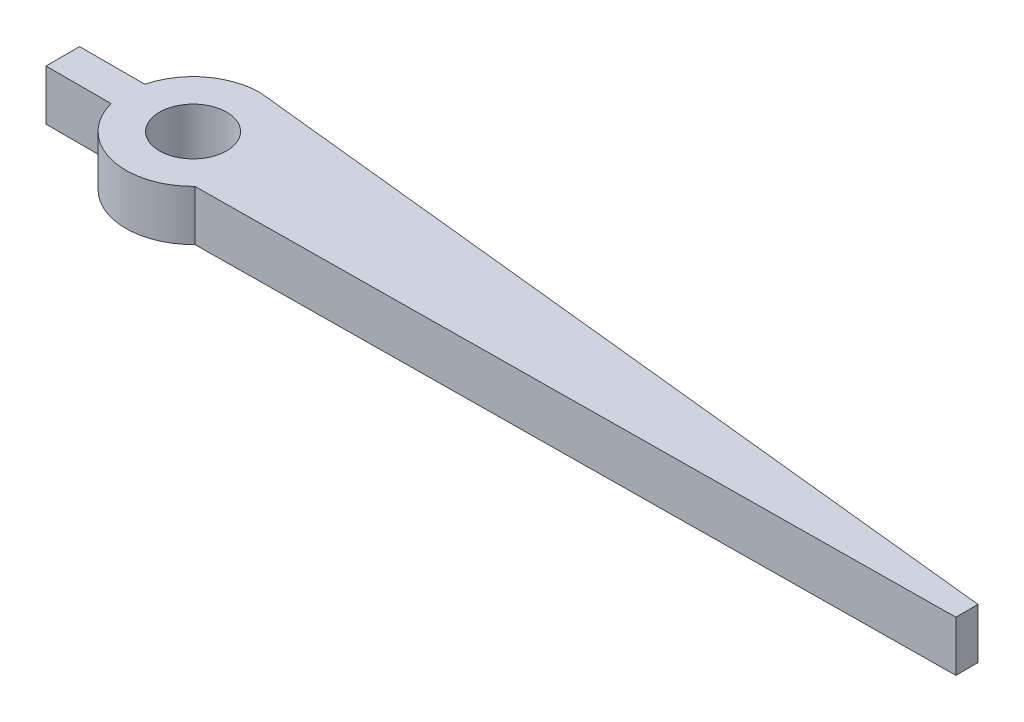
SolidWorks part; units mm, degrees
ref_plane "Front Plane" through (0, 0, 0) normal (0, 0, 1) x (1, 0, 0)
ref_plane "Top Plane" through (0, 0, 0) normal (0, 1, 0) x (1, 0, 0)
ref_plane "Right Plane" through (0, 0, 0) normal (1, 0, 0) x (0, 0, -1)
sketch "Sketch1" plane through (0, 0, 0) normal (0, 1, 0) x (1, 0, 0)
  line L0 (-40.4796, 15.6729) -> (-40.4796, 16.1729)
  line L1 (-40.4796, 15.6729) -> (-40.4796, 15.1729)
  line L2 (-44.3561, 16.1729) -> (-44.3561, 15.1729)
  line L3 (-42.4161, 15.1729) -> (-44.3561, 15.1729)
  line L4 (-42.4161, 16.1729) -> (-44.3561, 16.1729)
  line L5 (-40.4796, 17.6729) -> (-16.6111, 15.1642)
  line L6 (-16.6111, 15.1642) -> (-16.6111, 14.5052)
  line L7 (-39.0385, 14.2861) -> (-16.6111, 14.5052)
  circle A0 centre (-40.4796, 15.6729) radius 1
  circle A1 centre (-40.4796, 15.6729) radius 2
extrude "Boss-Extrude1" add sketch "Sketch1" along normal blind 1.5 contours A1 L7 L6 L5 | A1 L5 A0 | A1 L4 L2 L3
